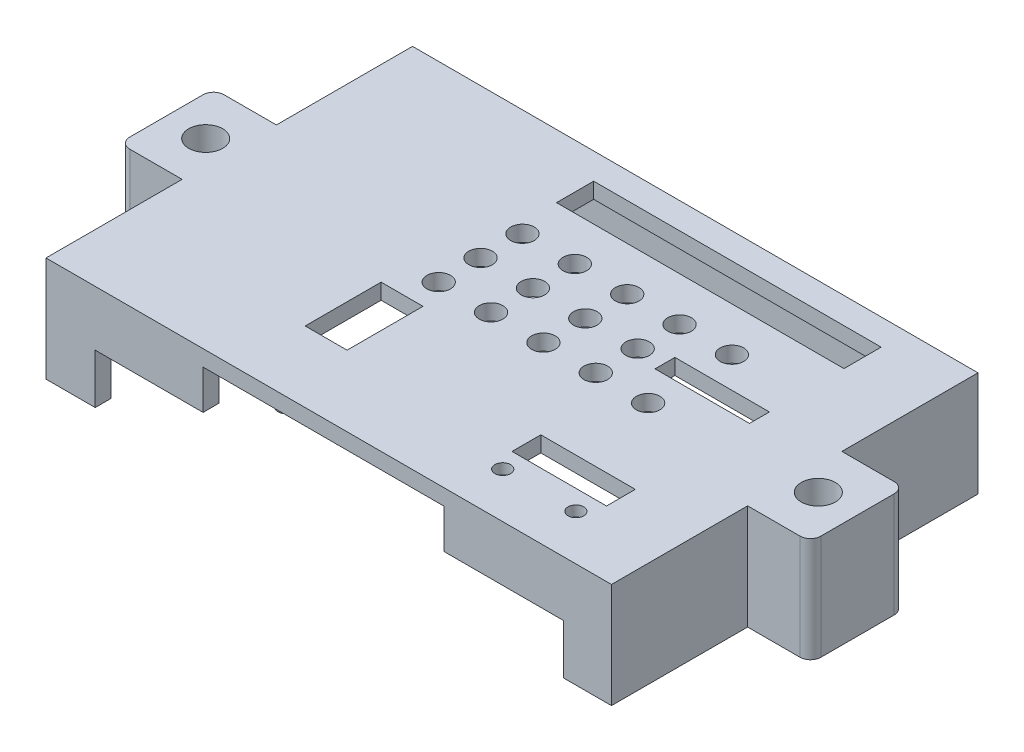
SolidWorks part; units mm, degrees
ref_plane "Front Plane" through (0, 0, 0) normal (0, 0, 1) x (1, 0, 0)
ref_plane "Top Plane" through (0, 0, 0) normal (0, 1, 0) x (1, 0, 0)
ref_plane "Right Plane" through (0, 0, 0) normal (1, 0, 0) x (0, 0, -1)
sketch "Sketch2" plane through (0, 0, 0) normal (0, 1, 0) x (1, 0, 0)
  line L0 (-37.2311, 32.3785) -> (37.7689, -6.6215) construction
  line L1 (-57.2311, 37.3785) -> (42.7689, 37.3785) construction
  line L2 (-57.2311, 37.3785) -> (-57.2311, -24.6215) construction
  line L3 (-57.2311, -24.6215) -> (42.7689, -24.6215) construction
  line L4 (42.7689, 37.3785) -> (42.7689, -24.6215) construction
  line L5 (-37.2311, -6.6215) -> (37.7689, 32.3785) construction
  line L7 (-58.2311, 38.3785) -> (43.7689, 38.3785) construction
  line L8 (-58.2311, 38.3785) -> (-58.2311, -25.6215) construction
  line L9 (-58.2311, -25.6215) -> (43.7689, -25.6215) construction
  line L10 (43.7689, 38.3785) -> (43.7689, -25.6215) construction
  line L11 (-61.2311, 41.3785) -> (46.7689, 41.3785)
  line L12 (-61.2311, 41.3785) -> (-61.2311, -28.6215)
  line L13 (-61.2311, -28.6215) -> (46.7689, -28.6215)
  line L14 (46.7689, 41.3785) -> (46.7689, -28.6215)
  line L15 (-25.2311, -0.6215) -> (-17.2311, -0.6215)
  line L16 (-25.2311, -0.6215) -> (-25.2311, -15.1215)
  line L17 (-25.2311, -15.1215) -> (-17.2311, -15.1215)
  line L18 (-17.2311, -0.6215) -> (-17.2311, -15.1215)
  circle A0 centre (20.2689, 4.8785) radius 2.25
  circle A1 centre (10.2689, 4.8785) radius 2.25
  circle A2 centre (0.2689, 4.8785) radius 2.25
  circle A3 centre (10.2689, 12.8785) radius 2.25
  circle A4 centre (0.2689, 12.8785) radius 2.25
  circle A5 centre (10.2689, 20.8785) radius 2.25
  circle A6 centre (0.2689, 20.8785) radius 2.25
  circle A7 centre (20.2689, 12.8785) radius 2.25
  circle A8 centre (20.2689, 20.8785) radius 2.25
  circle A9 centre (-9.7311, 4.8785) radius 2.25
  circle A10 centre (-9.7311, 12.8785) radius 2.25
  circle A11 centre (-9.7311, 20.8785) radius 2.25
  circle A12 centre (-19.7311, 4.8785) radius 2.25
  circle A13 centre (-19.7311, 12.8785) radius 2.25
  circle A14 centre (-19.7311, 20.8785) radius 2.25
  point P4 (-37.2311, 32.3785)
  point P5 (37.7689, 32.3785)
  point P6 (37.7689, -6.6215)
  point P7 (-37.2311, -6.6215)
  point P9 (20.2689, 4.8785)
  point P38 (-37.2311, 32.3785)
  point P41 (0.2689, 12.8785)
  dimension "D11" = 4.5
  dimension "D12" = 5
  dimension "D1" = 62
  dimension "D2" = 100
  dimension "D3" = 5
  dimension "D4" = 20
  dimension "D5" = 5
  dimension "D6" = 5
  dimension "D7" = 18
  dimension "D8" = 20
  dimension "D9" = 18
  dimension "D10" = 5
  dimension "D13" = 3
  dimension "D14" = 1
  dimension "D15" = 3
  dimension "D16" = 1
  dimension "D17" = 3
  dimension "D18" = 1
  dimension "D19" = 3
  dimension "D20" = 1
  dimension "D21" = 3
  dimension "D22" = 10.5
  dimension "D23" = 33
  dimension "D24" = 61
  dimension "D25" = 39
extrude "Boss-Extrude1" add sketch "Sketch2" along normal blind 3 contours L14 L11 L12 L13 A14 A13 A12 A11 A10 A9 A8 A7 A6 A5 A4 A3 A2 A1 A0 L15 L18 L17 L16 | A7
sketch "Sketch5" plane through (0, 0, 0) normal (0, -1, 0) x (-1, 0, 0)
  circle A0 centre (37.2311, 32.3785) radius 3.5635
  circle A1 centre (-37.7689, 32.3785) radius 3.5635
  circle A2 centre (-37.7689, -6.6215) radius 3.5635
  circle A3 centre (37.2311, -6.6215) radius 3.5635
  circle A4 centre (37.2311, 32.3785) radius 1.6865
  circle A5 centre (-37.7689, 32.3785) radius 1.6865
  circle A6 centre (-37.7689, -6.6215) radius 1.6865
  circle A7 centre (37.2311, -6.6215) radius 1.6865
  dimension "D1" = 7.127
  dimension "D4" = 3.373
  dimension "D2" = 2
  dimension "D3" = 2
extrude "Boss-Extrude2" add sketch "Sketch5" along normal blind 17
sketch "Sketch6" plane through (0, 0, 0) normal (0, -1, 0) x (-1, 0, 0)
  circle A0 centre (37.2311, 32.3785) radius 1.6865
  circle A4 centre (37.2311, 32.3785) radius 1.6865 construction
  circle A5 centre (-37.7689, 32.3785) radius 1.6865
  circle A6 centre (-37.7689, -6.6215) radius 1.6865
  circle A7 centre (37.2311, -6.6215) radius 1.6865
  circle A8 centre (-37.7689, 32.3785) radius 1.6865 construction
  dimension "D1" = 2
  dimension "D2" = 2
extrude "Boss-Extrude3" add sketch "Sketch6" along normal blind 20.6
sketch "Sketch7" plane through (0, 0, 0) normal (0, -1, 0) x (-1, 0, 0)
  line L1 (-43.7689, 38.3785) -> (58.2311, 38.3785)
  line L10 (-43.7689, 38.3785) -> (-43.7689, -25.6215)
  line L11 (-43.7689, -25.6215) -> (58.2311, -25.6215)
  line L12 (58.2311, 38.3785) -> (58.2311, -25.6215)
  line L13 (-46.7689, 41.3785) -> (61.2311, 41.3785)
  line L14 (-46.7689, 41.3785) -> (-46.7689, -28.6215)
  line L15 (-46.7689, -28.6215) -> (61.2311, -28.6215)
  line L16 (61.2311, 41.3785) -> (61.2311, -28.6215)
extrude "Boss-Extrude4" add sketch "Sketch7" along normal blind 17.05
sketch "Sketch8" plane through (0, -17.05, 0) normal (0, -1, 0) x (1, 0, 0)
  line L0 (-61.2311, 28.6215) -> (46.7689, 28.6215) construction
  line L1 (-58.2311, 25.6215) -> (43.7689, 25.6215) construction
  line L2 (-51.8311, 28.6215) -> (37.5689, 28.6215)
  line L3 (-51.8311, 28.6215) -> (-51.8311, 25.6215)
  line L4 (-51.8311, 25.6215) -> (37.5689, 25.6215)
  line L5 (37.5689, 28.6215) -> (37.5689, 25.6215)
  line L6 (-58.2311, -38.3785) -> (-58.2311, 25.6215) construction
  line L7 (43.7689, -38.3785) -> (43.7689, 25.6215) construction
  dimension "D1" = 6.4
  dimension "D2" = 6.2
extrude "Cut-Extrude1" cut sketch "Sketch8" against normal blind 9.5
sketch "Sketch9" plane through (0, -17.05, 0) normal (0, -1, 0) x (1, 0, 0)
  line L0 (-61.2311, 28.6215) -> (46.7689, 28.6215) construction
  line L1 (-31.2311, 28.6215) -> (14.7689, 28.6215)
  line L2 (-31.2311, 28.6215) -> (-31.2311, 25.6215)
  line L3 (-31.2311, 25.6215) -> (14.7689, 25.6215)
  line L4 (14.7689, 28.6215) -> (14.7689, 25.6215)
  line L5 (-58.2311, 25.6215) -> (43.7689, 25.6215) construction
  line L6 (-58.2311, -38.3785) -> (-58.2311, 25.6215) construction
  line L7 (43.7689, -38.3785) -> (43.7689, 25.6215) construction
  dimension "D1" = 27
  dimension "D2" = 29
extrude "Cut-Extrude2" cut sketch "Sketch9" against normal blind 17
sketch "Sketch10" plane through (0, 3, 0) normal (0, 1, 0) x (1, 0, 0)
  line L0 (-58.2311, 38.3785) -> (43.7689, 38.3785) construction
  line L1 (-21.6311, 36.3785) -> (33.2689, 36.3785)
  line L2 (-21.6311, 36.3785) -> (-21.6311, 29.2785)
  line L3 (-21.6311, 29.2785) -> (33.2689, 29.2785)
  line L4 (33.2689, 36.3785) -> (33.2689, 29.2785)
  line L5 (-58.2311, -25.6215) -> (43.7689, -25.6215) construction
  line L6 (43.7689, 38.3785) -> (43.7689, -25.6215) construction
  line L7 (-58.2311, 38.3785) -> (-58.2311, -25.6215) construction
  point P10 (33.2689, 32.8285)
  dimension "D1" = 2
  dimension "D2" = 54.9
  dimension "D3" = 10.5
  dimension "D4" = 36.6
extrude "Cut-Extrude3" cut sketch "Sketch10" against normal through all
sketch "Sketch11" plane through (-58.2311, 0, 0) normal (1, 0, 0) x (0, 0, -1)
  line L1 (-8.6215, -8.525) -> (-12.1183, -8.525) construction
  line L3 (6.3785, 0) -> (6.3785, -17.05) construction
  line L4 (38.3785, 0) -> (-25.6215, 0) construction
  line L6 (6.3785, -8.525) -> (10.6216, -8.525) construction
  circle A0 centre (-8.6215, -8.525) radius 3.4968
  circle A2 centre (21.3785, -8.525) radius 3.4968
  point P2 (6.3785, 0)
  dimension "D1" = 3.4968
  dimension "D2" = 15
extrude "Cut-Extrude4" cut sketch "Sketch11" against normal through all
sketch "Sketch12" plane through (-61.2311, 0, 0) normal (-1, 0, 0) x (0, 0, 1)
  line L0 (-6.3785, 0) -> (-6.3785, -17.05) construction
  line L1 (-29.7794, 0) -> (17.0224, 0)
  line L2 (-29.7794, 0) -> (-29.7794, -17.05)
  line L3 (-29.7794, -17.05) -> (17.0224, -17.05)
  line L4 (17.0224, 0) -> (17.0224, -17.05)
  line L6 (8.6215, -8.525) -> (8.6215, -12.0218) construction
  line L7 (-6.3785, -8.525) -> (-10.6216, -8.525) construction
  line L8 (-15.3785, 0) -> (2.6215, 0)
  line L9 (-15.3785, 0) -> (-15.3785, -17.05)
  line L10 (-15.3785, -17.05) -> (2.6215, -17.05)
  line L11 (2.6215, 0) -> (2.6215, -17.05)
  line L12 (0.2206, -1.1764) -> (17.0224, -1.1764) construction
  circle A0 centre (8.6215, -8.525) radius 3.4968 construction
  point P6 (-6.3785, -17.05)
  point P12 (-29.7794, -8.525)
  point P16 (-6.3785, 0)
  point P24 (8.6215, -1.1764)
  dimension "D1" = 18
  dimension "D2" = 46.8017
extrude "Cut-Extrude5" cut sketch "Sketch12" against normal blind 1
sketch "Sketch14" plane through (0, 3, 0) normal (0, 1, 0) x (1, 0, 0)
  line L1 (33.3189, 14.9885) -> (15.2689, 14.9885)
  line L6 (33.3189, 14.9885) -> (33.3189, 11.1885)
  line L7 (33.3189, 11.1885) -> (15.2689, 11.1885)
  line L16 (15.2689, 14.9885) -> (15.2689, 11.1885)
  line L17 (33.3189, -10.6215) -> (15.2689, -10.6215)
  line L18 (33.3189, -10.6215) -> (33.3189, -16.1215)
  line L19 (33.3189, -16.1215) -> (15.2689, -16.1215)
  line L20 (15.2689, -10.6215) -> (15.2689, -16.1215)
  line L21 (33.8189, -28.6215) -> (14.7689, -28.6215) construction
  line L22 (33.8189, -28.6215) -> (33.8189, 16.1885) construction
  line L23 (14.7689, -28.6215) -> (14.7689, 16.1885) construction
  line L24 (33.8189, 16.1885) -> (14.7689, 16.1885) construction
  line L25 (46.7689, 41.3785) -> (46.7689, -28.6215) construction
  line L26 (-61.2311, -28.6215) -> (46.7689, -28.6215) construction
  line L32 (14.7689, -25.6215) -> (14.7689, -28.6215) construction
  circle A3 centre (31.2789, -19.9315) radius 1.5
  circle A5 centre (17.3089, -19.9315) radius 1.5
  point P37 (0.2494, 0.2494)
  dimension "D14" = 3
  dimension "D24" = 8.69
  dimension "D12" = 19.05
  dimension "D13" = 44.81
  dimension "D15" = 2.54
  dimension "D16" = 12.5
  dimension "D17" = 18
  dimension "D18" = 1.2
  dimension "D19" = 5
  dimension "D20" = 1
  dimension "D21" = 1
  dimension "D22" = 8.69
  dimension "D23" = 2.54
extrude "Cut-Extrude7" cut sketch "Sketch14" against normal through all
sketch "Sketch15" plane through (0, 0, 0) normal (0, -1, 0) x (1, 0, 0)
  circle A0 centre (17.3089, 19.9315) radius 2.5
  circle A1 centre (31.2789, 19.9315) radius 2.5
  dimension "D1" = 5
  dimension "D2" = 5
extrude "Cut-Extrude10" cut sketch "Sketch15" against normal blind 1
sketch "Sketch17" plane through (0, -17.05, 0) normal (0, -1, 0) x (1, 0, 0)
  line L0 (-61.2311, -6.3785) -> (-69.1301, -6.3785) construction
  line L1 (-61.2311, 2.6215) -> (-61.2311, -15.3785) construction
  line L2 (-60.2311, -15.3785) -> (-61.2311, -15.3785) construction
  line L3 (-61.2311, 2.6215) -> (-73.2311, 2.6215)
  line L4 (-61.2311, 2.6215) -> (-61.2311, -15.3785)
  line L5 (-61.2311, -15.3785) -> (-73.2311, -15.3785)
  line L6 (-73.2311, 2.6215) -> (-73.2311, -15.3785)
  line L7 (-7.2311, -24.5092) -> (-7.2311, -58.2478) construction
  line L9 (46.7689, -15.3785) -> (58.7689, -15.3785)
  line L10 (58.7689, 2.6215) -> (58.7689, -15.3785)
  line L11 (46.7689, 2.6215) -> (58.7689, 2.6215)
  line L12 (46.7689, 2.6215) -> (46.7689, -15.3785)
  line L13 (46.7689, -41.3785) -> (46.7689, 28.6215) construction
  circle A0 centre (-65.7311, -6.3785) radius 3.25
  circle A1 centre (51.2689, -6.3785) radius 3.25
  point P16 (-7.2311, -41.3785)
  dimension "D1" = 18
  dimension "D3" = 7.5
  dimension "D2" = 12
  dimension "D4" = 7.5
extrude "Boss-Extrude5" add sketch "Sketch17" against normal up to surface (20.05 mm away)
fillet "Fillet1" radius 2 4 edges at (-73.2311, -7.025, -15.3785) (-73.2311, -7.025, 2.6215) (58.7689, -7.025, -15.3785) (58.7689, -7.025, 2.6215)
